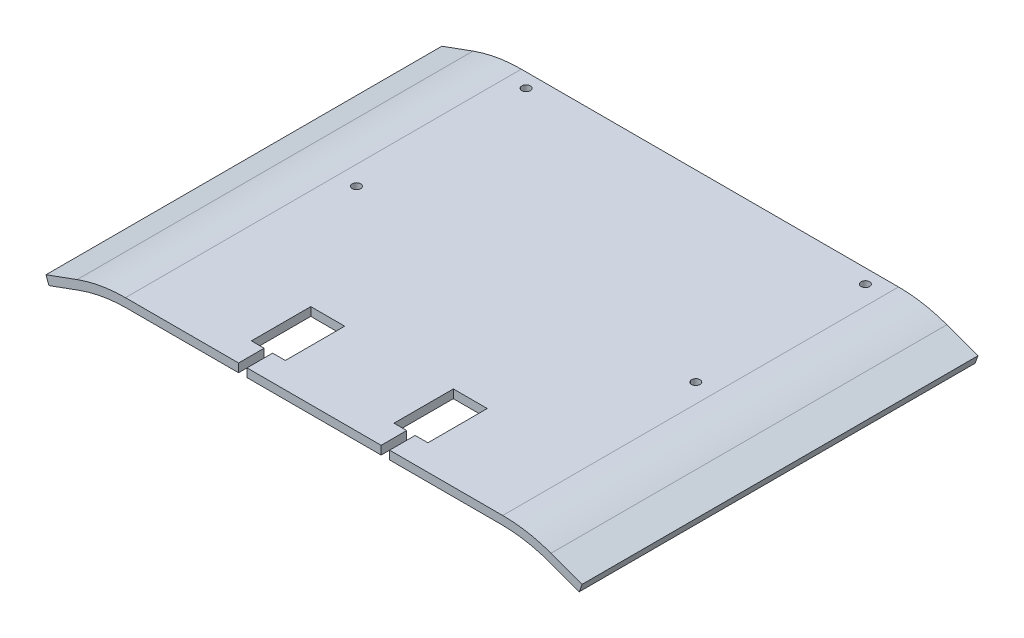
SolidWorks part; units mm, degrees
ref_plane "Front Plane" through (0, 0, 0) normal (0, 0, 1) x (1, 0, 0)
ref_plane "Top Plane" through (0, 0, 0) normal (0, 1, 0) x (1, 0, 0)
ref_plane "Right Plane" through (0, 0, 0) normal (1, 0, 0) x (0, 0, -1)
sketch "Sketch1" plane through (0, 0, 0) normal (0, 0, 1) x (1, 0, 0)
  line L0 (0, 0) -> (150, 0)
  line L1 (150, 0) -> (168.7939, -6.8404)
  line L2 (0, 0) -> (-18.7939, -6.8404)
  line L3 (168.7939, -6.8404) -> (169.8199, -4.0213)
  line L4 (169.8199, -4.0213) -> (150.529, 3)
  line L5 (150.529, 3) -> (-0.529, 3)
  line L6 (-0.529, 3) -> (-19.8199, -4.0213)
  line L7 (-19.8199, -4.0213) -> (-18.7939, -6.8404)
  point P3 (-19.3069, -5.4309)
  dimension "D1" = 160
  dimension "D2" = 160
  dimension "D3" = 20
  dimension "D4" = 20
  dimension "D5" = 150
  dimension "D6" = 3
  dimension "D7" = 1.5
  dimension "D8" = 3
  dimension "D9" = 90
  dimension "D10" = 3
extrude "Boss-Extrude1" add sketch "Sketch1" along normal blind 140
fillet "Fillet1" radius 50 2 edges at (-0.529, 3, 70) (150.529, 3, 70)
fillet "Fillet2" radius 50 2 edges at (0, 0, 70) (150, 0, 70)
sketch "Sketch3" plane through (0, 3, 0) normal (0, 1, 0) x (1, 0, 0)
  line L0 (101.7126, -140) -> (101.7126, -130.9607)
  line L1 (141.7126, -140) -> (8.2874, -140) construction
  line L2 (101.7126, -130.9607) -> (106.2126, -130.9607)
  line L3 (106.2126, -130.9607) -> (106.2126, -109.9607)
  line L4 (106.2126, -109.9607) -> (94.2126, -109.9607)
  line L5 (94.2126, -109.9607) -> (94.2126, -130.9607)
  line L6 (94.2126, -130.9607) -> (98.7126, -130.9607)
  line L7 (98.7126, -130.9607) -> (98.7126, -140)
  line L8 (98.7126, -140) -> (101.7126, -140)
  line L9 (51.2874, -140) -> (51.2874, -130.9607)
  line L10 (51.2874, -130.9607) -> (55.7874, -130.9607)
  line L11 (55.7874, -130.9607) -> (55.7874, -109.9607)
  line L12 (55.7874, -109.9607) -> (43.7874, -109.9607)
  line L13 (43.7874, -109.9607) -> (43.7874, -130.9607)
  line L14 (43.7874, -130.9607) -> (48.2874, -130.9607)
  line L15 (48.2874, -130.9607) -> (48.2874, -140)
  line L16 (48.2874, -140) -> (51.2874, -140)
  dimension "D1" = 12
  dimension "D2" = 3
  dimension "D3" = 4.5
  dimension "D4" = 21
  dimension "D5" = 21
  dimension "D6" = 4.5
  dimension "D7" = 40
  dimension "D8" = 12
  dimension "D9" = 3
  dimension "D10" = 4.5
  dimension "D11" = 4.5
  dimension "D12" = 21
  dimension "D13" = 21
  dimension "D14" = 40
extrude "Cut-Extrude1" cut sketch "Sketch3" against normal blind 150
sketch "Sketch4" plane through (0, 3, 0) normal (0, 1, 0) x (1, 0, 0)
  line L0 (141.7126, 0) -> (8.2874, 0) construction
  line L1 (141.7126, -140) -> (141.7126, 0) construction
  line L2 (8.2874, 0) -> (8.2874, -140) construction
  circle A0 centre (134.9974, -5) radius 1.5
  circle A1 centre (14.9974, -5) radius 1.5
  circle A2 centre (135.0026, -65) radius 1.5
  circle A3 centre (14.9974, -65) radius 1.5
  dimension "D1" = 3
  dimension "D2" = 3
  dimension "D3" = 3
  dimension "D4" = 3
  dimension "D5" = 5
  dimension "D6" = 5
  dimension "D7" = 6.71
  dimension "D8" = 6.71
  dimension "D9" = 120.0053
  dimension "D10" = 6.71
  dimension "D11" = 120
  dimension "D12" = 6.7153
  dimension "D13" = 60
  dimension "D14" = 60
extrude "Cut-Extrude2" cut sketch "Sketch4" against normal blind 10
sketch "Sketch5" plane through (0, 3, 0) normal (0, 1, 0) x (1, 0, 0)
  circle A0 centre (14.9974, -5) radius 3
  circle A1 centre (14.9974, -5) radius 1.5
  circle A2 centre (134.9974, -5) radius 3
  circle A3 centre (134.9974, -5) radius 1.5
  circle A4 centre (135.0026, -65) radius 3
  circle A5 centre (135.0026, -65) radius 1.5
  circle A6 centre (14.9974, -65) radius 3
  circle A7 centre (14.9974, -65) radius 1.5
  dimension "D1" = 3
  dimension "D2" = 6
  dimension "D3" = 3
  dimension "D4" = 6
  dimension "D5" = 3
  dimension "D6" = 6
  dimension "D7" = 3
  dimension "D8" = 6
extrude "Boss-Extrude2" add sketch "Sketch5" against normal blind 12
